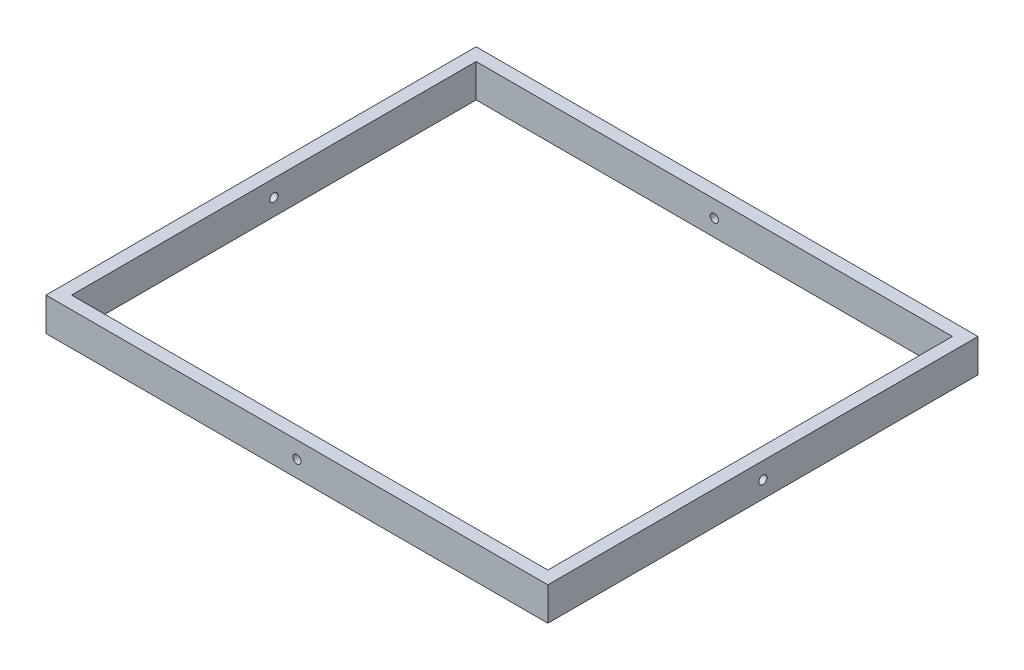
SolidWorks part; units mm, degrees
ref_plane "Front Plane" through (0, 0, 0) normal (0, 0, 1) x (1, 0, 0)
ref_plane "Top Plane" through (0, 0, 0) normal (0, 1, 0) x (1, 0, 0)
ref_plane "Right Plane" through (0, 0, 0) normal (1, 0, 0) x (0, 0, -1)
sketch "Sketch1" plane through (0, 0, 0) normal (0, 1, 0) x (1, 0, 0)
  line L1 (-173.8893, 63.1966) -> (137.2607, 63.1966)
  line L2 (-173.8893, 63.1966) -> (-173.8893, -203.5034)
  line L3 (-173.8893, -203.5034) -> (137.2607, -203.5034)
  line L4 (137.2607, 63.1966) -> (137.2607, -203.5034)
  line L5 (-165.9518, 55.2591) -> (129.3232, 55.2591)
  line L6 (-165.9518, 55.2591) -> (-165.9518, -195.5659)
  line L7 (-165.9518, -195.5659) -> (129.3232, -195.5659)
  line L8 (129.3232, 55.2591) -> (129.3232, -195.5659)
  dimension "D1" = 311.15
  dimension "D2" = 266.7
  dimension "D3" = 7.9375
  dimension "D4" = 7.9375
  dimension "D5" = 7.9375
  dimension "D6" = 7.9375
extrude "Boss-Extrude1" add sketch "Sketch1" along normal blind 20.6375
sketch "Sketch2" plane through (0, 0, 203.5034) normal (0, 0, 1) x (1, 0, 0)
  line L0 (-173.8893, 10.3187) -> (137.2607, 10.3187) construction
  line L1 (-173.8893, 20.6375) -> (-173.8893, 0) construction
  line L2 (137.2607, 20.6375) -> (137.2607, 0) construction
  circle A0 centre (-18.3143, 10.3187) radius 2.54
extrude "Cut-Extrude1" cut sketch "Sketch2" against normal through all
sketch "Sketch3" plane through (137.2607, 0, 0) normal (1, 0, 0) x (0, 0, -1)
  line L0 (-203.5034, 10.3187) -> (63.1966, 10.3187) construction
  line L1 (-203.5034, 20.6375) -> (-203.5034, 0) construction
  line L2 (63.1966, 20.6375) -> (63.1966, 0) construction
  circle A0 centre (-70.1534, 10.3187) radius 2.54
extrude "Cut-Extrude2" cut sketch "Sketch3" against normal through all
